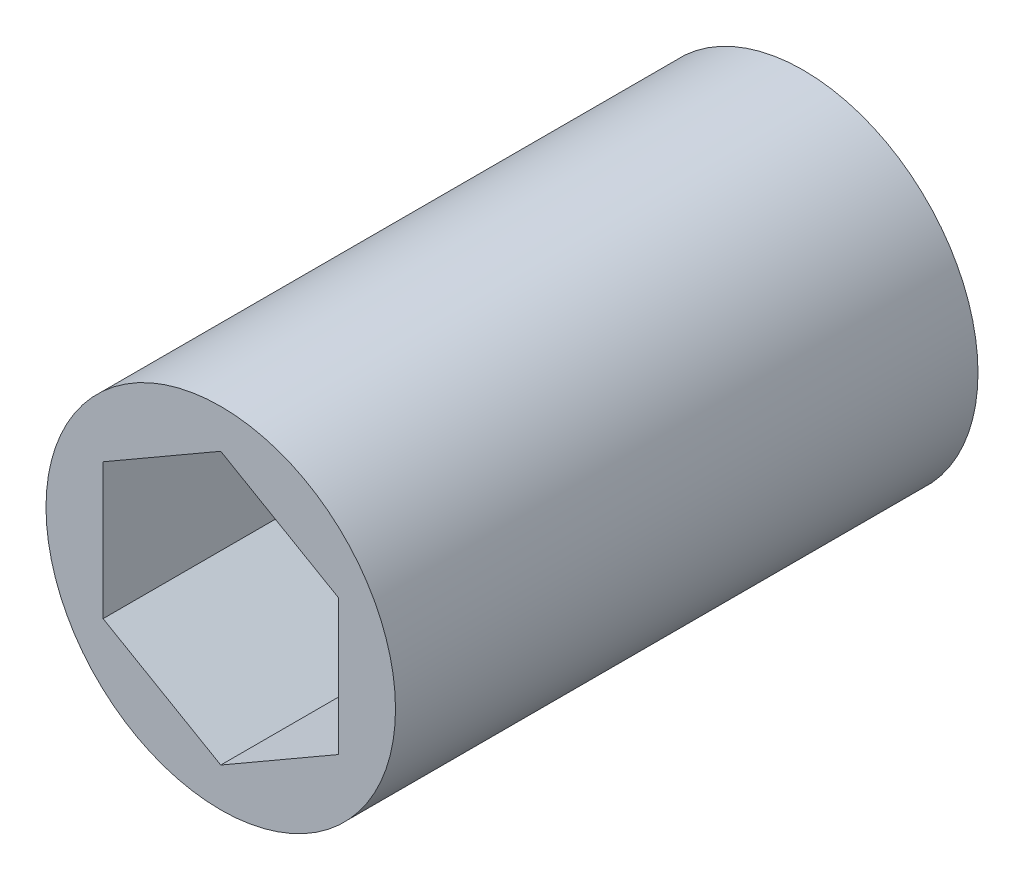
SolidWorks part; units mm, degrees
material "PET"
ref_plane "Front Plane" through (0, 0, 0) normal (0, 0, 1) x (1, 0, 0)
ref_plane "Top Plane" through (0, 0, 0) normal (0, 1, 0) x (1, 0, 0)
ref_plane "Right Plane" through (0, 0, 0) normal (1, 0, 0) x (0, 0, -1)
sketch "Sketch2" plane through (0, 0, 0) normal (0, 0, 1) x (1, 0, 0)
  line L1 (6.4135, 3.7028) -> (0, 7.4057)
  line L2 (0, 7.4057) -> (-6.4135, 3.7028)
  line L3 (-6.4135, 3.7028) -> (-6.4135, -3.7028)
  line L4 (-6.4135, -3.7028) -> (0, -7.4057)
  line L5 (0, -7.4057) -> (6.4135, -3.7028)
  line L6 (6.4135, -3.7028) -> (6.4135, 3.7028)
  circle A0 centre (0, 0) radius 9.525
  circle A1 centre (0, 0) radius 6.4135 construction
  dimension "D1" = 12.827
  dimension "D2" = 19.05
extrude "Boss-Extrude1" add sketch "Sketch2" along normal blind 31.75
